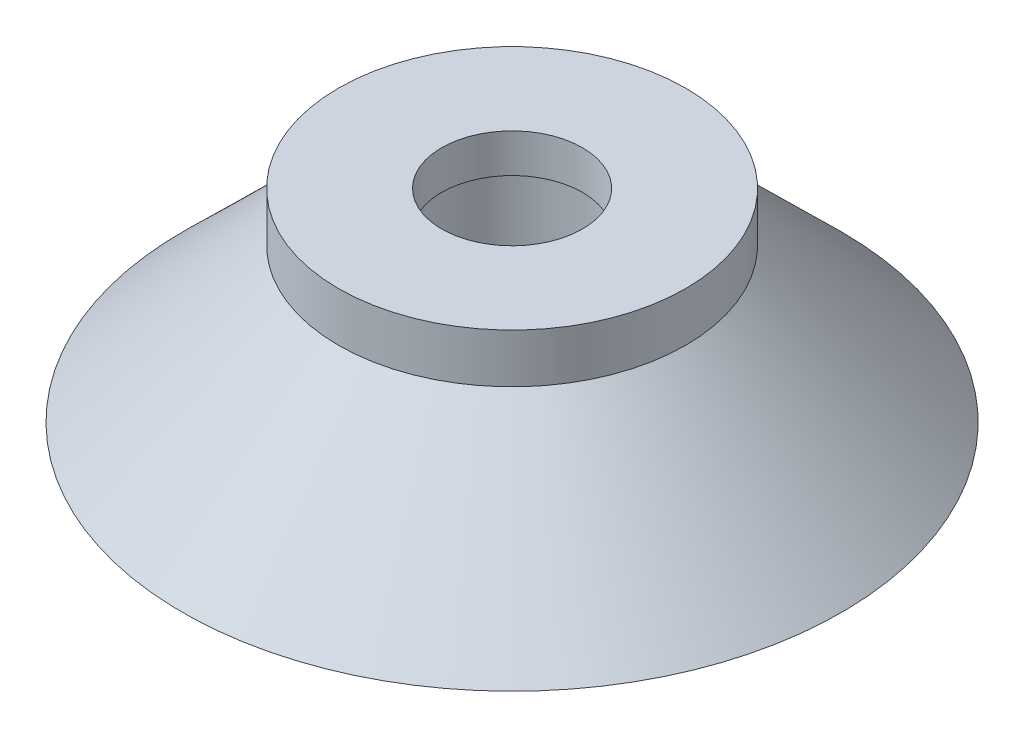
SolidWorks part; units mm, degrees
ref_plane "Front Plane" through (0, 0, 0) normal (0, 0, 1) x (1, 0, 0)
ref_plane "Top Plane" through (0, 0, 0) normal (0, 1, 0) x (1, 0, 0)
ref_plane "Right Plane" through (0, 0, 0) normal (1, 0, 0) x (0, 0, -1)
sketch "Sketch1" plane through (0, 0, 0) normal (1, 0, 0) x (0, 0, -1)
  line L0 (0, 0) -> (0, 7.85) construction
  line L1 (2.73, 6.35) -> (2.73, 7.85)
  line L2 (2.73, 7.85) -> (6.73, 7.85)
  line L3 (6.73, 7.85) -> (6.73, 5.945)
  line L4 (6.73, 5.945) -> (12.7762, 0)
  line L5 (12.7762, 0) -> (3.2, 0)
  line L6 (2.73, 6.35) -> (3.2, 6.35)
  line L7 (3.2, 6.35) -> (3.2, 0)
  point P3 (0, 0)
  dimension "D1" = 4
  dimension "D2" = 5.46
  dimension "D3" = 3.2
  dimension "D4" = 1.905
  dimension "D5" = 12.7762
  dimension "D6" = 6.35
  dimension "D7" = 1.5
revolve "Revolve1" add sketch "Sketch1" angle 360 about L0
